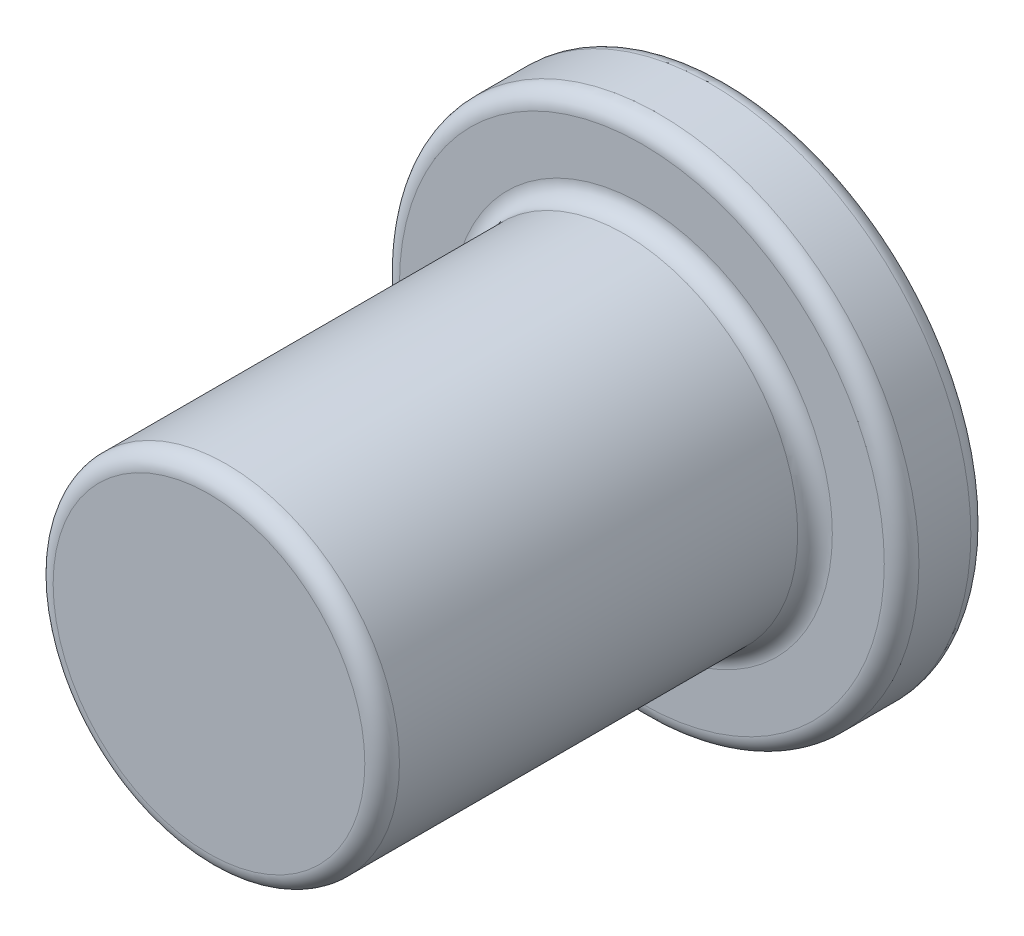
SolidWorks part; units mm, degrees
ref_plane "Front Plane" through (0, 0, 0) normal (0, 0, 1) x (1, 0, 0)
ref_plane "Top Plane" through (0, 0, 0) normal (0, 1, 0) x (1, 0, 0)
ref_plane "Right Plane" through (0, 0, 0) normal (1, 0, 0) x (0, 0, -1)
sketch "Sketch1" plane through (0, 0, 0) normal (0, 0, 1) x (1, 0, 0)
  circle A0 centre (0, 0) radius 3
  dimension "D1" = 6
extrude "Boss-Extrude1" add sketch "Sketch1" along normal mid plane 1
sketch "Sketch2" plane through (0, 0, 0.5) normal (0, 0, 1) x (1, 0, 0)
  circle A0 centre (0, 0) radius 2
  dimension "D1" = 4
extrude "Boss-Extrude2" add sketch "Sketch2" along normal blind 5
fillet "Fillet1" radius 0.2 4 edges at (2, 0, 0.5) (2, 0, 5.5) (3, 0, 0.5) (3, 0, -0.5)
